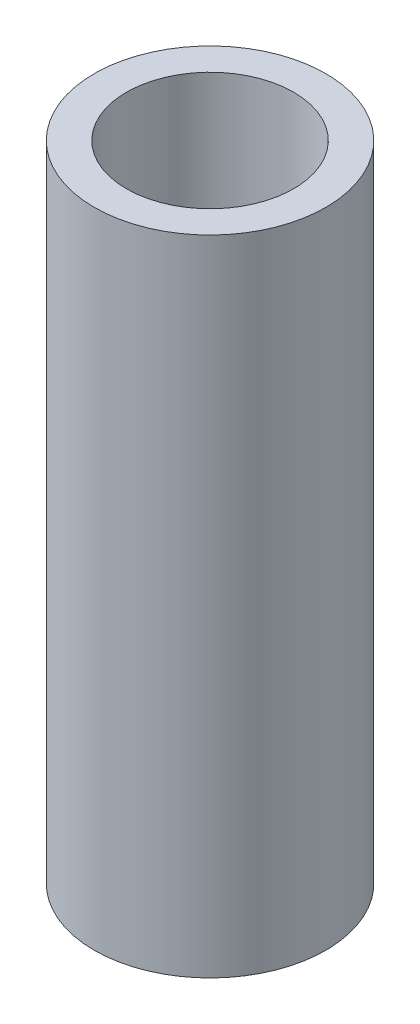
SolidWorks part; units mm, degrees
ref_plane "Front Plane" through (0, 0, 0) normal (0, 0, 1) x (1, 0, 0)
ref_plane "Top Plane" through (0, 0, 0) normal (0, 1, 0) x (1, 0, 0)
ref_plane "Right Plane" through (0, 0, 0) normal (1, 0, 0) x (0, 0, -1)
sketch "草圖1" plane through (0, 0, 0) normal (0, 1, 0) x (1, 0, 0)
  circle A0 centre (0, 0) radius 4.5
  circle A1 centre (0, 0) radius 3.25
  dimension "D1" = 9
  dimension "D2" = 6.5
extrude "填料-伸長1" add sketch "草圖1" along normal blind 25
